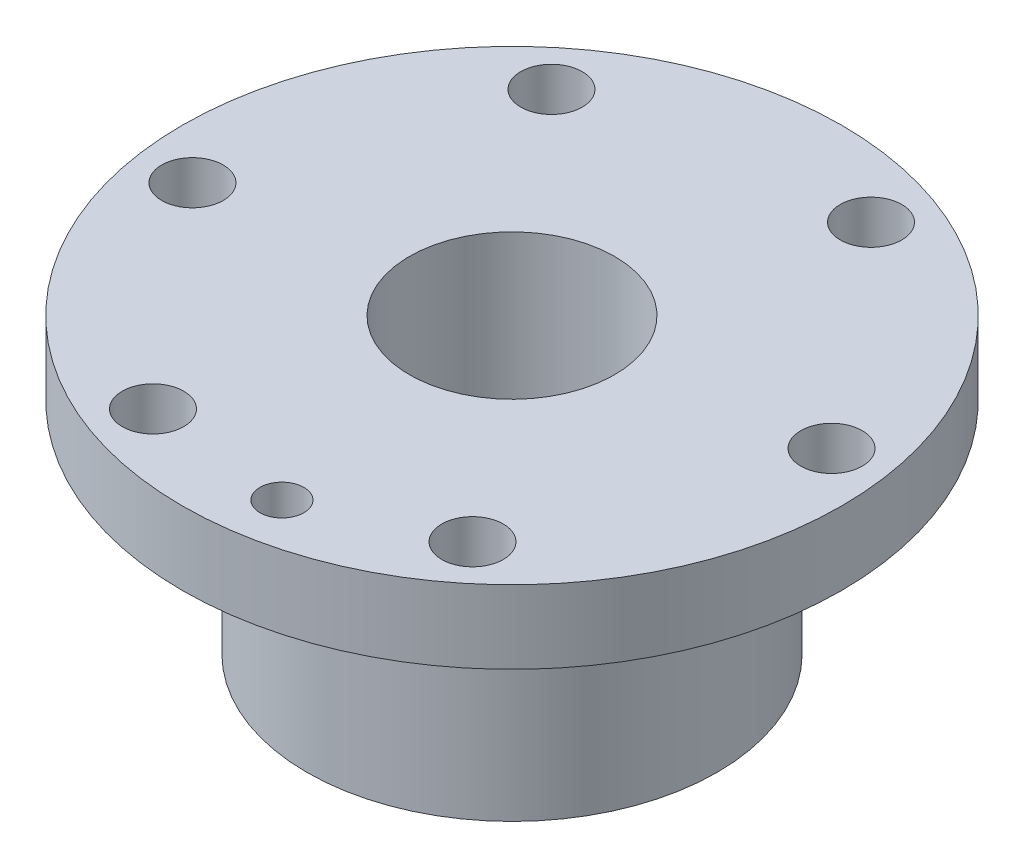
SolidWorks part; units mm, degrees
ref_plane "Front Plane" through (0, 0, 0) normal (0, 0, 1) x (1, 0, 0)
ref_plane "Top Plane" through (0, 0, 0) normal (0, 1, 0) x (1, 0, 0)
ref_plane "Right Plane" through (0, 0, 0) normal (1, 0, 0) x (0, 0, -1)
sketch "Sketch1" plane through (0, 0, 0) normal (0, 1, 0) x (1, 0, 0)
  circle A0 centre (0, 0) radius 30
  circle A1 centre (0, 0) radius 15.2 construction
  dimension "D1" = 60
extrude "Boss-Extrude1" add sketch "Sketch1" along normal blind 5
sketch "Sketch2" plane through (0, 0, 0) normal (0, -1, 0) x (-1, 0, 0)
  circle A0 centre (12.02, 14.7146) radius 2.1
  circle A1 centre (-6.7333, 17.7669) radius 2.1
  circle A2 centre (-18.7532, 3.0523) radius 2.1
  circle A3 centre (-12.02, -14.7146) radius 2.1
  circle A4 centre (-3.0523, -18.7532) radius 1.5
  circle A5 centre (6.7333, -17.7669) radius 2.1
  circle A6 centre (18.7532, -3.0523) radius 2.1
  circle A7 centre (0, 0) radius 22.5
  circle A8 centre (0, 0) radius 30
  circle M1 centre (0, 0) radius 30
  dimension "D1" = 45
extrude "Cut-Extrude1" cut sketch "Sketch2" against normal blind 10 contours A7 M1 | A0 | A1 | A2 | A3 | A4 | A5 | A6
sketch "Sketch3" plane through (0, 0, 0) normal (0, -1, 0) x (1, 0, 0)
  circle A0 centre (0, 0) radius 14
  dimension "D1" = 28
extrude "Boss-Extrude2" add sketch "Sketch3" along normal blind 15
sketch "Sketch4" plane through (0, -15, 0) normal (0, -1, 0) x (1, 0, 0)
  circle A0 centre (-0.9789, 9.952) radius 2
  circle A1 centre (-9.952, -0.9789) radius 2
  circle A2 centre (0.9789, -9.952) radius 2
  circle A3 centre (9.952, 0.9789) radius 2
extrude "Cut-Extrude2" cut sketch "Sketch4" against normal blind 6
sketch "Sketch5" plane through (0, -15, 0) normal (0, -1, 0) x (1, 0, 0)
  circle A0 centre (0, 0) radius 7
extrude "Cut-Extrude3" cut sketch "Sketch5" against normal through all
